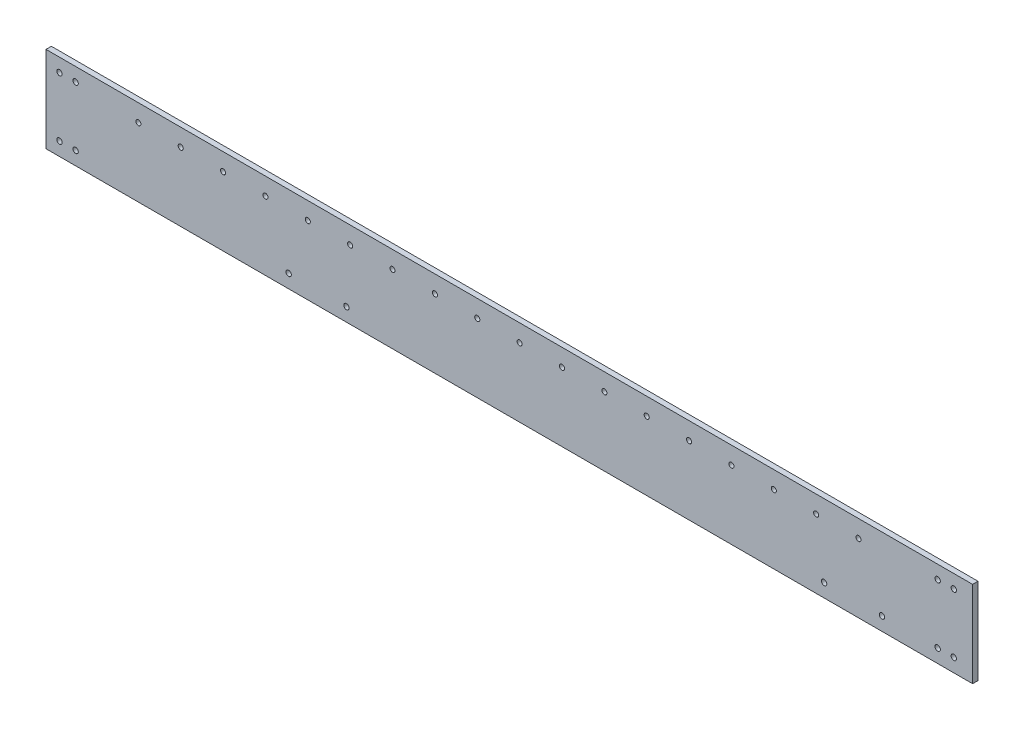
SolidWorks part; units mm, degrees
ref_plane "Front Plane" through (0, 0, 0) normal (0, 0, 1) x (1, 0, 0)
ref_plane "Top Plane" through (0, 0, 0) normal (0, 1, 0) x (1, 0, 0)
ref_plane "Right Plane" through (0, 0, 0) normal (1, 0, 0) x (0, 0, -1)
sketch "Sketch1" plane through (0, 0, 0) normal (1, 0, 0) x (0, 0, -1)
  line L0 (0, 0) -> (-3.175, 0)
  line L3 (-3.175, 0) -> (-3.175, 50.8)
  line L4 (-3.175, 50.8) -> (0, 50.8)
  line L5 (0, 50.8) -> (0, 0)
  dimension "LHeight" = 50.8
  dimension "LMaterialThickness" = 3.175
extrude "Boss-Extrude1" add sketch "Sketch1" along normal blind 546.825
sketch "SideHoles-Sketch4" plane through (0, 0, 3.175) normal (0, 0, 1) x (1, 0, 0)
  line L1 (546.825, 50.8) -> (546.825, 0) construction
  line L2 (0, 50.8) -> (0, 0) construction
  line L3 (546.825, 50.8) -> (0, 50.8) construction
  line L4 (546.825, 0) -> (0, 0) construction
  line L5 (546.825, 50.8) -> (0, 50.8) construction
  line L6 (0, 50.8) -> (0, 0) construction
  line L7 (546.825, 50.8) -> (546.825, 0) construction
  circle A1 centre (7.9375, 42.8625) radius 1.5875
  circle A3 centre (526.1875, 42.8625) radius 1.5875
  circle A4 centre (17.4625, 42.8625) radius 1.5875
  circle A5 centre (535.7125, 42.8625) radius 1.5875
  circle A6 centre (7.9375, 7.9375) radius 1.5875
  circle A7 centre (17.4625, 7.9375) radius 1.5875
  circle A8 centre (526.1875, 7.9375) radius 1.5875
  circle A9 centre (535.7125, 7.9375) radius 1.5875
  circle A10 centre (54.5, 40.575) radius 1.5
  circle A11 centre (79.5, 40.575) radius 1.5
  circle A12 centre (104.5, 40.575) radius 1.5
  circle A13 centre (129.5, 40.575) radius 1.5
  circle A14 centre (154.5, 40.575) radius 1.5
  circle A15 centre (179.5, 40.575) radius 1.5
  circle A16 centre (204.5, 40.575) radius 1.5
  circle A17 centre (229.5, 40.575) radius 1.5
  circle A18 centre (254.5, 40.575) radius 1.5
  circle A19 centre (279.5, 40.575) radius 1.5
  circle A20 centre (304.5, 40.575) radius 1.5
  circle A21 centre (329.5, 40.575) radius 1.5
  circle A22 centre (354.5, 40.575) radius 1.5
  circle A23 centre (379.5, 40.575) radius 1.5
  circle A24 centre (493.3125, 7.9375) radius 1.5875
  circle A26 centre (177.3125, 7.9375) radius 1.5875
  circle A29 centre (404.5, 40.575) radius 1.5
  circle A30 centre (429.5, 40.575) radius 1.5
  circle A31 centre (454.5, 40.575) radius 1.5
  circle A32 centre (479.5, 40.575) radius 1.5
  circle A34 centre (143.1875, 7.9375) radius 1.5875
  circle A36 centre (459.1875, 7.9375) radius 1.5875
  dimension "D2" = 3.175
  dimension "D10" = 3
  dimension "D14" = 3.175
  dimension "D4" = 7.9375
  dimension "D3" = 11.1125
  dimension "D5" = 20.6375
  dimension "D1" = 7.9375
  dimension "D6" = 17.4625
  dimension "D7" = 7.9375
  dimension "D9" = 10.225
  dimension "D8" = 54.5
  dimension "D12" = 25
  dimension "D15" = 7.9375
  dimension "D17" = 53.5125
  dimension "D18" = 316
  dimension "D13" = 34.125
  dimension "D16" = 34.125
  dimension "D11" = 18
extrude "SideHoles-Cut-Extrude3" cut sketch "SideHoles-Sketch4" against normal through all
equation "\"MidLeftOrRightSideRailHeight\"= 2.0in"
equation "\"RailThickness\"= .125in'Spec"
equation "\"SideRailHoleY1FromEdge\"= \"HoleOffsetFromEdge\""
equation "\"SideRailHoleX1FromSide\"= \"HoleOffsetFromSide\""
equation "\"MidSideRailLength\"= \"SideRailLength\" - \"RailThickness\"'Equals 546.825 => MidSideRail buts up against MidBackRail"
equation "\"VSWidth\"= 1.25in'Spec"
equation "\"HoleOffsetFromEdge\"= \"RailThickness\" * 2.5"
equation "\"HoleOffsetFromSide\"= \"RailThickness\" * 3.5"
equation "\"SideRailHoleX2FromSide\"= \"VSWidth\" - \"HoleOffsetFromEdge\" - \"RailThickness\"'Equals 20.6375"
equation "\"FasteningHoleDiameter\"= .125in"
equation "\"StepperWidth\"= 42mm'Spec"
equation "\"D2@SideHoles-Sketch4\"=\"FasteningHoleDiameter\""
equation "\"LHeight@Sketch1\"=\"MidLeftOrRightSideRailHeight\""
equation "\"LMaterialThickness@Sketch1\"=\"RailThickness\""
equation "\"D1@Boss-Extrude1\"=\"MidSideRailLength\""
equation "\"D4@SideHoles-Sketch4\"=\"SideRailHoleY1FromEdge\""
equation "\"D3@SideHoles-Sketch4\"=\"SideRailHoleX1FromSide\" "
equation "\"D5@SideHoles-Sketch4\"=\"SideRailHoleX2FromSide\" "
equation "\"D1@SideHoles-Sketch4\"=\"SideRailHoleX1FromSide\" -\"RailThickness\""
equation "\"D6@SideHoles-Sketch4\"=\"SideRailHoleX2FromSide\"-\"RailThickness\""
equation "\"LinearRailXMountHole\"= \"StepperWidth\" + \"LinearRailFirstHoleOffsetFromEdge\""
equation "\"D9@SideHoles-Sketch4\"=\"V6.3 GantryMiddleToToTopOfMidSideRail\""
equation "\"D8@SideHoles-Sketch4\"=\"LinearRailXMountHole\""
equation "\"LinearRailHoleDistance\"= 25mm'Spec"
equation "\"D12@SideHoles-Sketch4\"=\"LinearRailHoleDistance\""
equation "\"SideRailLength\"= 550mm"
equation "\"LinearRailFirstHoleOffsetFromEdge\"= 12.5mm'Spec"
equation "\"D7@SideHoles-Sketch4\"= \"MidRailRodStabilizerMountingHoleOffsetFromEdge\""
equation "\"DistanceFromBedFrontToFirstLeftStepperHole\"= \"LeadScrewNutPadSize\" + 10mm'Equals 34"
equation "\"BeltTensionerDepth\"= \"BeltTensionerBackWallThickness\" + \"BeltTensionerInnerDepth\"'Equals 23.4"
equation "\"20TGT2PulleyDiameter\"= 17.9mm'Spec"
equation "\"BeltTensionerSpaceBetweenPulleyAndWall\"= 1.5mm"
equation "\"BeltTensionerBackWallThickness\"= 4mm"
equation "\"BeltTensionerInnerDepth\"= \"20TGT2PulleyDiameter\" + \"BeltTensionerSpaceBetweenPulleyAndWall\""
equation "\"DistanceFromFrontSideToBedFront\"= \"RailThickness\" + \"BeltTensionerDepth\" + 10mm'Equals 36.575"
equation "\"DistanceBetweenFrontToBackStepperHoles\"= \"BedLength\" - \"DistanceFromBedFrontToFirstLeftStepperHole\"'Equals 316"
equation "\"BedLength\"= \"BedInnerSquareLength\" + \"BedLWidth\" * 2 - \"BedOverlap\" * 2 + \"BedIncreasedByLength\"'Equals 350"
equation "\"BedOverlap\"= 20mm"
equation "\"BedThirdSize\"= 70mm"
equation "\"BedInnerSquareWidth\"= \"BedThirdSize\" * 3'Equals 210"
equation "\"BedLWidth\"= \"BedThirdSize\" + \"BedOverlap\"'Equals 90"
equation "\"BedIncreasedByLength\"= 0mm"
equation "\"D14@SideHoles-Sketch4\"= \"FasteningHoleDiameter\""
equation "\"D15@SideHoles-Sketch4\"= \"HoleOffsetFromEdge\""
equation "\"BedInnerSquareLength\"= \"BedInnerSquareWidth\""
equation "\"GABMidWallHeight\"= 28mm'Must equal 28 or changes alignment"
equation "\"20TGT2PulleyWidth\"= 8.7mm'The STL of the Pulley in the diagram is a bit larger"
equation "\"GABMidShortRiserHeight\"= \"GABMidWallHeight\" / 2 - \"20TGT2PulleyWidth\"'Equals 5.3"
equation "\"GABUpperHeight\"= 6mm"
equation "\"GABLowerHeight\"= 3mm"
equation "\"GABRiserBossOffset\"= 0.8mm'Aligns Pulleys"
equation "\"GABHeight\"= \"GABLowerHeight\" + \"GABMidWallHeight\" + \"GABUpperHeight\""
equation "\"StepperShaftLength\"= 24mm'Pulley will be attached to the end"
equation "\"V6.1 FromGantryPulleyToGantryMiddle\"= \"GABHeight\" / 2 - \"GABMidShortRiserHeight\" - \"GABLowerHeight\" + \"GABRiserBossOffset\" / 2"
equation "\"V6.2 GantryMiddleToTopOfMidBackRail\"= \"StepperShaftLength\" - \"V6.1 FromGantryPulleyToGantryMiddle\""
equation "\"V6.3 GantryMiddleToToTopOfMidSideRail\"= \"V6.2 GantryMiddleToTopOfMidBackRail\" - \"RailThickness\""
equation "\"DistanceFromFrontSideToFirstLeftStabilizerMountingHole\"= \"DistanceFromFrontSideToFirstLeftStepperHole\" - \"DistanceFromStepperHoleToRodStabilizerMountingHole\"'Equals 53.5125"
equation "\"DistanceFromFrontSideToFirstLeftStepperHole\"= \"DistanceFromFrontSideToBedFront\" + \"DistanceFromBedFrontToFirstLeftStepperHole\"'Equals 70.575"
equation "\"LeadScrewNutMountingHoleFlangeDiameter\"= 22mm'Spec"
equation "\"LeadScrewNutPadSize\"= \"LeadScrewNutMountingHoleFlangeDiameter\" + 2mm'Equals 24"
equation "\"D17@SideHoles-Sketch4\"=\"DistanceFromFrontSideToFirstLeftStabilizerMountingHole\""
equation "\"D18@SideHoles-Sketch4\"=\"DistanceBetweenFrontToBackStepperHoles\""
equation "\"MidRailRodStabilizerMountingHoleOffsetFromEdge\"= \"HoleOffsetFromEdge\""
equation "\"RodStabilizerLength\"= 50mm"
equation "\"DistanceFromStepperHoleToRodStabilizerMountingHole\"= \"RodStabilizerLength\" / 2 - \"HoleOffsetFromEdge\"'Equals 17.0625"
equation "\"D13@SideHoles-Sketch4\"=\"RodStabilizerLength\" - \"HoleOffsetFromEdge\" * 2"
equation "\"D16@SideHoles-Sketch4\"=\"RodStabilizerLength\" - \"HoleOffsetFromEdge\" *2"
